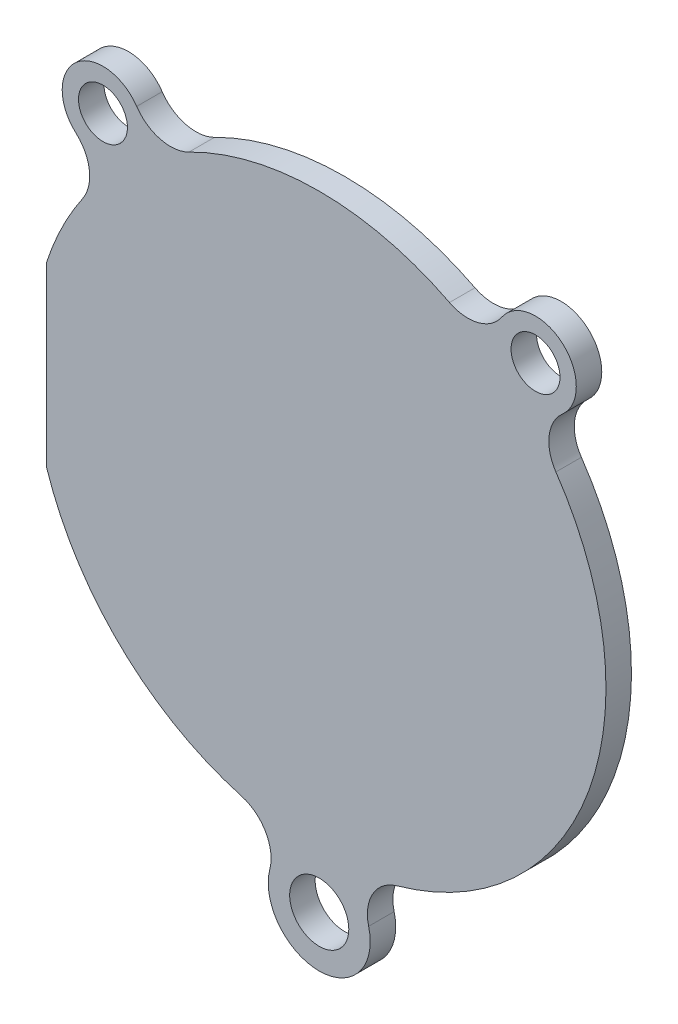
SolidWorks part; units mm, degrees
ref_plane "Front Plane" through (0, 0, 0) normal (0, 0, 1) x (1, 0, 0)
ref_plane "Top Plane" through (0, 0, 0) normal (0, 1, 0) x (1, 0, 0)
ref_plane "Right Plane" through (0, 0, 0) normal (1, 0, 0) x (0, 0, -1)
sketch "Sketch1" plane through (0, 0, 0) normal (0, 0, 1) x (1, 0, 0)
  line L7 (-16.9841, -5.5245) -> (-16.9841, 5.5245)
  arc A0 (-14.7417, 10.0827) -> (-15.1544, 13.4183) centre (-16.8382, 11.5166) ccw construction
  arc A1 (4.8506, -17.1887) -> (14.7417, 10.0827) centre (0, 0) ccw construction
  arc A2 (8.1137, 15.9106) -> (-8.1137, 15.9106) centre (0, 0) ccw construction
  arc A3 (4.8506, -17.1887) -> (3.078, -20.2562) centre (5.5404, -19.6332) ccw construction
  arc A4 (15.1544, 13.4183) -> (14.7417, 10.0827) centre (16.8382, 11.5166) ccw construction
  arc A5 (8.1137, 15.9106) -> (11.3691, 16.7466) centre (9.2677, 18.1733) ccw construction
  arc A6 (-3.078, -20.2562) -> (-4.8506, -17.1887) centre (-5.5404, -19.6332) ccw construction
  arc A7 (-14.7417, 10.0827) -> (-16.9841, 5.5245) centre (0, 0) ccw
  arc A8 (-16.9841, -5.5245) -> (-4.8506, -17.1887) centre (0, 0) ccw
  arc A9 (-3.078, -20.2562) -> (3.078, -20.2562) centre (0, -21.035) ccw construction
  arc A10 (4.8506, -17.1887) -> (14.7417, 10.0827) centre (0, 0) ccw
  arc A11 (-3.078, -20.2562) -> (-4.8506, -17.1887) centre (-5.5404, -19.6332) ccw
  arc A12 (8.1137, 15.9106) -> (-8.1137, 15.9106) centre (0, 0) ccw
  arc A13 (-3.078, -20.2562) -> (3.078, -20.2562) centre (0, -21.035) ccw
  arc A14 (4.8506, -17.1887) -> (3.078, -20.2562) centre (5.5404, -19.6332) ccw
  circle A15 centre (0, -21.035) radius 1.8415 construction
  circle A17 centre (0, -21.035) radius 1.8415
  arc A18 (-11.3691, 16.7466) -> (-15.1544, 13.4183) centre (-13.4706, 15.32) ccw construction
  circle A19 centre (-13.4706, 15.32) radius 1.524 construction
  arc A20 (-11.3691, 16.7466) -> (-8.1137, 15.9106) centre (-9.2677, 18.1733) ccw construction
  arc A22 (-14.7417, 10.0827) -> (-15.1544, 13.4183) centre (-16.8382, 11.5166) ccw
  arc A23 (-11.3691, 16.7466) -> (-15.1544, 13.4183) centre (-13.4706, 15.32) ccw
  circle A24 centre (-13.4706, 15.32) radius 1.524
  arc A25 (-11.3691, 16.7466) -> (-8.1137, 15.9106) centre (-9.2677, 18.1733) ccw
  arc A26 (15.1544, 13.4183) -> (11.3691, 16.7466) centre (13.4706, 15.32) ccw construction
  circle A27 centre (13.4706, 15.32) radius 1.524 construction
  arc A28 (15.1544, 13.4183) -> (11.3691, 16.7466) centre (13.4706, 15.32) ccw
  circle A29 centre (13.4706, 15.32) radius 1.524
  arc A30 (8.1137, 15.9106) -> (11.3691, 16.7466) centre (9.2677, 18.1733) ccw
  arc A31 (15.1544, 13.4183) -> (14.7417, 10.0827) centre (16.8382, 11.5166) ccw
extrude "Boss-Extrude1" add sketch "Sketch1" along normal blind 1.5875
